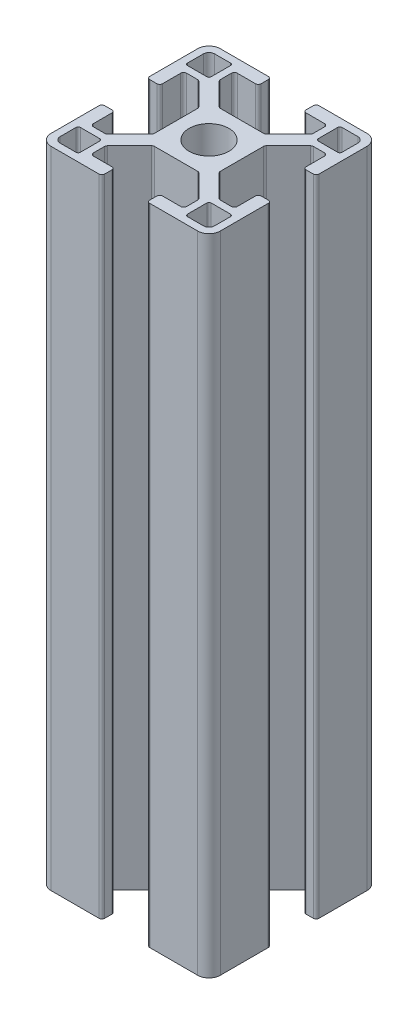
SolidWorks part; units mm, degrees
ref_plane "Front Plane" through (0, 0, 0) normal (0, 0, 1) x (1, 0, 0)
ref_plane "Top Plane" through (0, 0, 0) normal (0, 1, 0) x (1, 0, 0)
ref_plane "Right Plane" through (0, 0, 0) normal (1, 0, 0) x (0, 0, -1)
sketch "Sketch1" plane through (0, 0, 0) normal (0, 1, 0) x (1, 0, 0)
  line L0 (3.9799, -2.4733) -> (3.1981, -1.4942) construction
  line L1 (1.4942, -3.1981) -> (2.4733, -3.9799) construction
  line L2 (-2.4733, -3.9799) -> (-1.4942, -3.1981) construction
  line L3 (-3.1981, -1.4942) -> (-3.9799, -2.4733) construction
  line L4 (-3.9799, 2.4733) -> (-3.1981, 1.4942) construction
  line L5 (-1.4942, 3.1981) -> (-2.4733, 3.9799) construction
  line L6 (2.4733, 3.9799) -> (1.4942, 3.1981) construction
  line L7 (3.1981, 1.4942) -> (3.9799, 2.4733) construction
  line L8 (-12.6999, -13.6999) -> (-9.881, -13.6999)
  line L9 (-13.6999, -9.881) -> (-13.6999, -12.6999)
  line L10 (-9.88, -9.5) -> (-13.3189, -9.5)
  line L11 (-9.5, -13.3189) -> (-9.5, -9.88)
  line L12 (13.6999, -12.6999) -> (13.6999, -9.881)
  line L13 (9.881, -13.6999) -> (12.6999, -13.6999)
  line L14 (9.5, -9.88) -> (9.5, -13.3189)
  line L15 (13.3189, -9.5) -> (9.88, -9.5)
  line L16 (9.88, 9.5) -> (13.3189, 9.5)
  line L17 (9.5, 13.3189) -> (9.5, 9.88)
  line L18 (12.6999, 13.6999) -> (9.881, 13.6999)
  line L19 (13.6999, 9.881) -> (13.6999, 12.6999)
  line L20 (-13.6999, 12.6999) -> (-13.6999, 9.881)
  line L21 (-9.881, 13.6999) -> (-12.6999, 13.6999)
  line L22 (-9.5, 9.88) -> (-9.5, 13.3189)
  line L23 (-13.3189, 9.5) -> (-9.88, 9.5)
  line L24 (14.4999, -4) -> (13.2425, -4)
  line L25 (12.7425, -4.5) -> (12.7425, -7.7325)
  line L26 (12.2428, -8.25) -> (10.2602, -8.25)
  line L27 (9.9066, -8.1035) -> (5.9811, -4.178)
  line L28 (5.8347, -3.8245) -> (5.8347, -1.0125)
  line L29 (5.8347, -1.0125) -> (5.3247, -0.0625) construction
  line L30 (5.3247, -0.0625) -> (5.8347, 0.8875) construction
  line L31 (5.8347, 0.8875) -> (5.8347, 3.8245)
  line L32 (5.9811, 4.178) -> (9.9066, 8.1035)
  line L33 (10.2602, 8.25) -> (12.2428, 8.25)
  line L34 (12.7425, 7.7325) -> (12.7425, 4.5)
  line L35 (13.2425, 4) -> (14.4999, 4)
  line L36 (14.9999, 4.5) -> (14.9999, 12.9999)
  line L37 (12.9999, 14.9999) -> (4.5, 14.9999)
  line L38 (4, 14.4999) -> (4, 13.2425)
  line L39 (4.5, 12.7425) -> (7.7325, 12.7425)
  line L40 (8.25, 12.2428) -> (8.25, 10.2602)
  line L41 (8.1035, 9.9066) -> (4.178, 5.9811)
  line L42 (3.8245, 5.8347) -> (0.95, 5.8347)
  line L43 (0.95, 5.8347) -> (0, 5.3247) construction
  line L44 (0, 5.3247) -> (-0.95, 5.8347) construction
  line L45 (-0.95, 5.8347) -> (-3.8245, 5.8347)
  line L46 (-4.178, 5.9811) -> (-8.1035, 9.9066)
  line L47 (-8.25, 10.2602) -> (-8.25, 12.2428)
  line L48 (-7.7325, 12.7425) -> (-4.5, 12.7425)
  line L49 (-4, 13.2425) -> (-4, 14.4999)
  line L50 (-4.5, 14.9999) -> (-12.9999, 14.9999)
  line L51 (-14.9999, 12.9999) -> (-14.9999, 4.5)
  line L52 (-14.4999, 4) -> (-13.2425, 4)
  line L53 (-12.7425, 4.5) -> (-12.7425, 7.7325)
  line L54 (-12.2428, 8.25) -> (-10.2602, 8.25)
  line L55 (-9.9066, 8.1035) -> (-5.9811, 4.178)
  line L56 (-5.8347, 3.8245) -> (-5.8347, 0.8875)
  line L57 (-5.8347, 0.8875) -> (-5.3247, -0.0625) construction
  line L58 (-5.3247, -0.0625) -> (-5.8347, -1.0125) construction
  line L59 (-5.8347, -1.0125) -> (-5.8347, -3.8245)
  line L60 (-5.9811, -4.178) -> (-9.9066, -8.1035)
  line L61 (-10.2602, -8.25) -> (-12.2428, -8.25)
  line L62 (-12.7425, -7.7325) -> (-12.7425, -4.5)
  line L63 (-13.2425, -4) -> (-14.4999, -4)
  line L64 (-14.9999, -4.5) -> (-14.9999, -12.9999)
  line L65 (-12.9999, -14.9999) -> (-4.5, -14.9999)
  line L66 (-4, -14.4999) -> (-4, -13.2425)
  line L67 (-4.5, -12.7425) -> (-7.7325, -12.7425)
  line L68 (-8.25, -12.2428) -> (-8.25, -10.2602)
  line L69 (-8.1035, -9.9066) -> (-4.178, -5.9811)
  line L70 (-3.8245, -5.8347) -> (-0.95, -5.8347)
  line L71 (-0.95, -5.8347) -> (0, -5.3247) construction
  line L72 (0, -5.3247) -> (0.95, -5.8347) construction
  line L73 (0.95, -5.8347) -> (3.8245, -5.8347)
  line L74 (4.178, -5.9811) -> (8.1035, -9.9066)
  line L75 (8.25, -10.2602) -> (8.25, -12.2428)
  line L76 (7.7325, -12.7425) -> (4.5, -12.7425)
  line L77 (4, -13.2425) -> (4, -14.4999)
  line L78 (4.5, -14.9999) -> (12.9999, -14.9999)
  line L79 (14.9999, -12.9999) -> (14.9999, -4.5)
  line L80 (-5.8347, -1.0125) -> (-5.8347, 0.8875)
  line L81 (-0.95, 5.8347) -> (0.95, 5.8347)
  line L82 (5.8347, 0.8875) -> (5.8347, -1.0125)
  line L83 (-0.95, -5.8347) -> (0.95, -5.8347)
  arc A0 (2.4733, -3.9799) -> (3.9799, -2.4733) centre (3.1422, -3.1422) ccw construction
  arc A1 (-1.4942, -3.1981) -> (1.4942, -3.1981) centre (0, 0) ccw construction
  arc A2 (-3.9799, -2.4733) -> (-2.4733, -3.9799) centre (-3.1422, -3.1422) ccw construction
  arc A3 (-3.1981, 1.4942) -> (-3.1981, -1.4942) centre (0, 0) ccw construction
  arc A4 (-2.4733, 3.9799) -> (-3.9799, 2.4733) centre (-3.1422, 3.1422) ccw construction
  arc A5 (1.4942, 3.1981) -> (-1.4942, 3.1981) centre (0, 0) ccw construction
  arc A6 (3.9799, 2.4733) -> (2.4733, 3.9799) centre (3.1422, 3.1422) ccw construction
  arc A7 (3.1981, -1.4942) -> (3.1981, 1.4942) centre (0, 0) ccw construction
  arc A8 (-13.6999, -12.6999) -> (-12.6999, -13.6999) centre (-12.6999, -12.6999) ccw
  arc A9 (-13.3189, -9.5) -> (-13.6999, -9.881) centre (-13.3189, -9.881) ccw
  arc A10 (-9.5, -9.88) -> (-9.88, -9.5) centre (-9.88, -9.88) ccw
  arc A11 (-9.881, -13.6999) -> (-9.5, -13.3189) centre (-9.881, -13.3189) ccw
  arc A12 (12.6999, -13.6999) -> (13.6999, -12.6999) centre (12.6999, -12.6999) ccw
  arc A13 (9.5, -13.3189) -> (9.881, -13.6999) centre (9.881, -13.3189) ccw
  arc A14 (9.88, -9.5) -> (9.5, -9.88) centre (9.88, -9.88) ccw
  arc A15 (13.6999, -9.881) -> (13.3189, -9.5) centre (13.3189, -9.881) ccw
  arc A16 (9.5, 9.88) -> (9.88, 9.5) centre (9.88, 9.88) ccw
  arc A17 (9.881, 13.6999) -> (9.5, 13.3189) centre (9.881, 13.3189) ccw
  arc A18 (13.6999, 12.6999) -> (12.6999, 13.6999) centre (12.6999, 12.6999) ccw
  arc A19 (13.3189, 9.5) -> (13.6999, 9.881) centre (13.3189, 9.881) ccw
  arc A20 (14.9999, -4.5) -> (14.4999, -4) centre (14.4999, -4.5) ccw
  arc A21 (13.2425, -4) -> (12.7425, -4.5) centre (13.2425, -4.5) ccw
  arc A22 (12.2428, -8.25) -> (12.7425, -7.7325) centre (12.2428, -7.75) ccw
  arc A23 (9.9066, -8.1035) -> (10.2602, -8.25) centre (10.2602, -7.75) ccw
  arc A24 (5.8347, -3.8245) -> (5.9811, -4.178) centre (6.3347, -3.8245) ccw
  arc A25 (5.9811, 4.178) -> (5.8347, 3.8245) centre (6.3347, 3.8245) ccw
  arc A26 (10.2602, 8.25) -> (9.9066, 8.1035) centre (10.2602, 7.75) ccw
  arc A27 (12.7425, 7.7325) -> (12.2428, 8.25) centre (12.2428, 7.75) ccw
  arc A28 (12.7425, 4.5) -> (13.2425, 4) centre (13.2425, 4.5) ccw
  arc A29 (14.4999, 4) -> (14.9999, 4.5) centre (14.4999, 4.5) ccw
  arc A30 (14.9999, 12.9999) -> (12.9999, 14.9999) centre (12.9999, 12.9999) ccw
  arc A31 (4.5, 14.9999) -> (4, 14.4999) centre (4.5, 14.4999) ccw
  arc A32 (4, 13.2425) -> (4.5, 12.7425) centre (4.5, 13.2425) ccw
  arc A33 (8.25, 12.2428) -> (7.7325, 12.7425) centre (7.75, 12.2428) ccw
  arc A34 (8.1035, 9.9066) -> (8.25, 10.2602) centre (7.75, 10.2602) ccw
  arc A35 (3.8245, 5.8347) -> (4.178, 5.9811) centre (3.8245, 6.3347) ccw
  arc A36 (-4.178, 5.9811) -> (-3.8245, 5.8347) centre (-3.8245, 6.3347) ccw
  arc A37 (-8.25, 10.2602) -> (-8.1035, 9.9066) centre (-7.75, 10.2602) ccw
  arc A38 (-7.7325, 12.7425) -> (-8.25, 12.2428) centre (-7.75, 12.2428) ccw
  arc A39 (-4.5, 12.7425) -> (-4, 13.2425) centre (-4.5, 13.2425) ccw
  arc A40 (-4, 14.4999) -> (-4.5, 14.9999) centre (-4.5, 14.4999) ccw
  arc A41 (-12.9999, 14.9999) -> (-14.9999, 12.9999) centre (-12.9999, 12.9999) ccw
  arc A42 (-14.9999, 4.5) -> (-14.4999, 4) centre (-14.4999, 4.5) ccw
  arc A43 (-13.2425, 4) -> (-12.7425, 4.5) centre (-13.2425, 4.5) ccw
  arc A44 (-12.2428, 8.25) -> (-12.7425, 7.7325) centre (-12.2428, 7.75) ccw
  arc A45 (-9.9066, 8.1035) -> (-10.2602, 8.25) centre (-10.2602, 7.75) ccw
  arc A46 (-5.8347, 3.8245) -> (-5.9811, 4.178) centre (-6.3347, 3.8245) ccw
  arc A47 (-5.9811, -4.178) -> (-5.8347, -3.8245) centre (-6.3347, -3.8245) ccw
  arc A48 (-10.2602, -8.25) -> (-9.9066, -8.1035) centre (-10.2602, -7.75) ccw
  arc A49 (-12.7425, -7.7325) -> (-12.2428, -8.25) centre (-12.2428, -7.75) ccw
  arc A50 (-12.7425, -4.5) -> (-13.2425, -4) centre (-13.2425, -4.5) ccw
  arc A51 (-14.4999, -4) -> (-14.9999, -4.5) centre (-14.4999, -4.5) ccw
  arc A52 (-14.9999, -12.9999) -> (-12.9999, -14.9999) centre (-12.9999, -12.9999) ccw
  arc A53 (-4.5, -14.9999) -> (-4, -14.4999) centre (-4.5, -14.4999) ccw
  arc A54 (-4, -13.2425) -> (-4.5, -12.7425) centre (-4.5, -13.2425) ccw
  arc A55 (-8.25, -12.2428) -> (-7.7325, -12.7425) centre (-7.75, -12.2428) ccw
  arc A56 (-8.1035, -9.9066) -> (-8.25, -10.2602) centre (-7.75, -10.2602) ccw
  arc A57 (-3.8245, -5.8347) -> (-4.178, -5.9811) centre (-3.8245, -6.3347) ccw
  arc A58 (4.178, -5.9811) -> (3.8245, -5.8347) centre (3.8245, -6.3347) ccw
  arc A59 (8.25, -10.2602) -> (8.1035, -9.9066) centre (7.75, -10.2602) ccw
  arc A60 (7.7325, -12.7425) -> (8.25, -12.2428) centre (7.75, -12.2428) ccw
  arc A61 (4.5, -12.7425) -> (4, -13.2425) centre (4.5, -13.2425) ccw
  arc A62 (4, -14.4999) -> (4.5, -14.9999) centre (4.5, -14.4999) ccw
  arc A63 (12.9999, -14.9999) -> (14.9999, -12.9999) centre (12.9999, -12.9999) ccw
  arc A64 (-12.6999, 13.6999) -> (-13.6999, 12.6999) centre (-12.6999, 12.6999) ccw
  arc A65 (-9.5, 13.3189) -> (-9.881, 13.6999) centre (-9.881, 13.3189) ccw
  arc A66 (-9.88, 9.5) -> (-9.5, 9.88) centre (-9.88, 9.88) ccw
  arc A67 (-13.6999, 9.881) -> (-13.3189, 9.5) centre (-13.3189, 9.881) ccw
  circle A68 centre (0, 0) radius 3.53
extrude "Boss-Extrude1" add sketch "Sketch1" along normal mid plane 114.3
